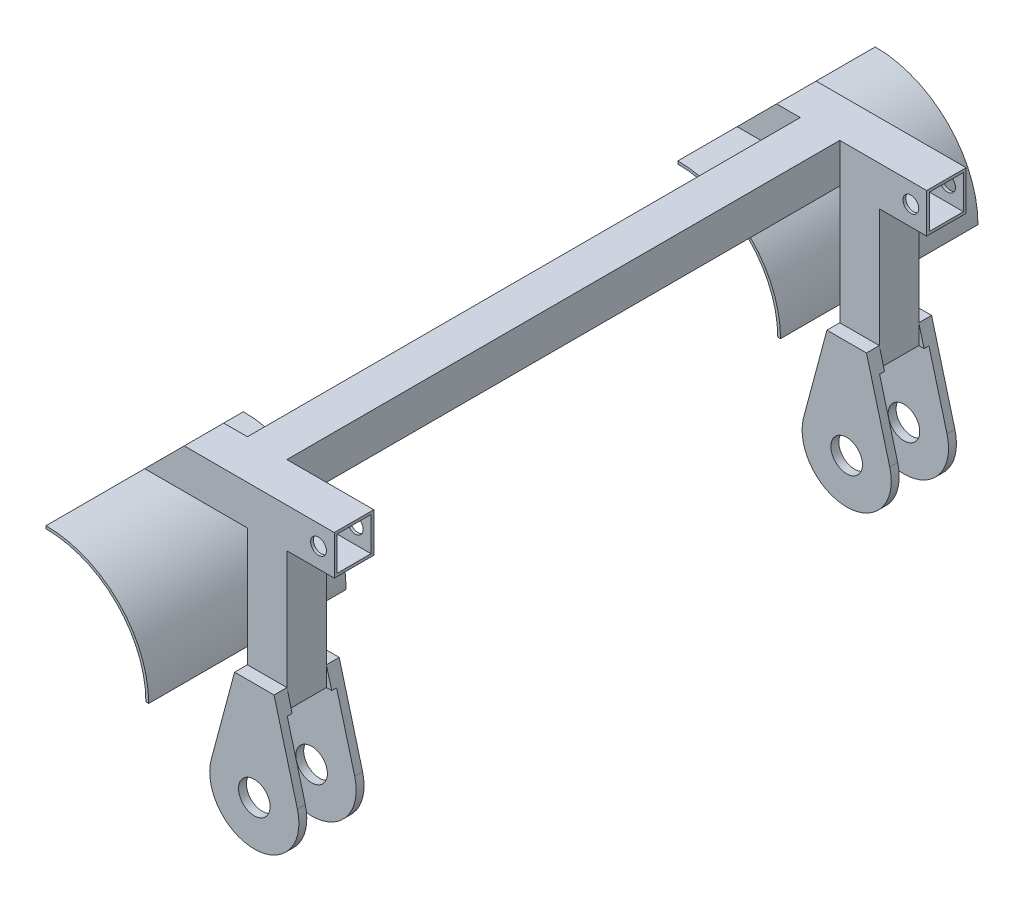
SolidWorks part; units mm, degrees
ref_plane "Front Plane" through (0, 0, 0) normal (0, 0, 1) x (1, 0, 0)
ref_plane "Top Plane" through (0, 0, 0) normal (0, 1, 0) x (1, 0, 0)
ref_plane "Right Plane" through (0, 0, 0) normal (1, 0, 0) x (0, 0, -1)
sketch "Sketch1" plane through (0, 0, 0) normal (0, 0, 1) x (1, 0, 0)
  line L0 (0, -11.2927) -> (0, 37.1736) construction
  line L1 (-5, 25) -> (5, 25)
  line L2 (-5, 25) -> (-10.9089, 2.9192)
  line L3 (5, 25) -> (10.9089, 2.9192)
  circle A0 centre (0, 0) radius 4
  arc A1 (-10.9089, 2.9192) -> (10.9089, 2.9192) centre (0, 0) ccw
  point P9 (0, 25)
  dimension "D1" = 8
  dimension "D2" = 5
  dimension "D3" = 25
extrude "Boss-Extrude1" add sketch "Sketch1" along normal blind 2 and the other way blind 1.25
sketch "Sketch2" plane through (0, 0, 2) normal (0, 0, 1) x (1, 0, 0)
  line L0 (-5, 55) -> (-5, 20)
  line L1 (-5, 20) -> (5, 20)
  line L2 (5, 20) -> (5, 55)
  line L3 (5, 55) -> (-5, 55)
  line L4 (5, 25) -> (-5, 25) construction
  dimension "D1" = 55
  dimension "D2" = 5
extrude "Boss-Extrude2" add sketch "Sketch2" along normal blind 10
ref_plane "Plane1" through (0, 0, 7) normal (0, 0, 1) x (1, 0, 0)
mirror "Mirror1" about plane through (0, 0, 7) normal (0, 0, 1) of bodies 102
ref_plane "Plane2" through (17, 0, 0) normal (1, 0, 0) x (0, 0, -1)
sketch "Sketch4" plane through (17, 0, 0) normal (1, 0, 0) x (0, 0, -1)
  line L0 (-11.3, 64.3) -> (-2.7, 64.3)
  line L1 (-12, 55) -> (-2, 55)
  line L2 (-12, 55) -> (-12, 65)
  line L3 (-12, 65) -> (-2, 65)
  line L4 (-2, 55) -> (-2, 65)
  line L5 (-2.7, 55.7) -> (-2.7, 64.3)
  line L6 (-11.3, 55.7) -> (-2.7, 55.7)
  line L7 (-11.3, 55.7) -> (-11.3, 64.3)
  dimension "D1" = 10
  dimension "D2" = 10
  dimension "D3" = 0.7
extrude "Boss-Extrude3" add sketch "Sketch4" against normal blind 48
sketch "Sketch5" plane through (0, 0, 12) normal (0, 0, 1) x (1, 0, 0)
  line L0 (17, -5.5) -> (17, 5.5) construction
  line L1 (5, 55) -> (17, 55) construction
  circle A0 centre (13, 60) radius 2
  dimension "D1" = 4
  dimension "D2" = 5
extrude "Cut-Extrude1" cut sketch "Sketch5" against normal blind 50
sketch "Sketch9" plane through (0, 0, 12) normal (0, 0, 1) x (1, 0, 0)
  line L0 (-5, 55) -> (-5, 25) construction
  line L1 (-31, 55) -> (-5, 55)
  line L2 (-31, 55) -> (-31, 54.3)
  line L3 (-5.7, 29) -> (-5, 29)
  line L4 (-5, 55) -> (-5, 29)
  arc A0 (-5, 29) -> (-31, 55) centre (-31, 29) ccw
  arc A1 (-5.7, 29) -> (-31, 54.3) centre (-31, 29) ccw
  circle A2 centre (-31, 29) radius 26 construction
  circle A3 centre (-31, 29) radius 25.3 construction
  dimension "D1" = 26
  dimension "D2" = 0.7
extrude "Boss-Extrude4" add sketch "Sketch9" along normal mid plane 50 separate body contours A1 L3 A0 L2
sketch "Sketch10" plane through (0, 0, 12) normal (0, 0, 1) x (1, 0, 0)
  line L0 (-31, 65) -> (-31, 55)
  line L1 (-31, 55) -> (-21, 65)
  line L2 (-31, 65) -> (17, 65) construction
  line L3 (-21, 65) -> (-31, 65)
extrude "Cut-Extrude2" cut sketch "Sketch10" against normal blind 50
ref_plane "Plane3" through (0, 0, -68) normal (0, 0, -1) x (-1, 0, 0)
sketch "Sketch14" plane through (5, 0, 0) normal (1, 0, 0) x (0, 0, -1)
  line L1 (-2, 20) -> (-0.75, 20)
  line L2 (-2, 20) -> (-2, -14.9033)
  line L3 (-2, -14.9033) -> (-0.75, -14.9033)
  line L4 (-0.75, 20) -> (-0.75, -14.9033)
  line L5 (-12, 20) -> (-13.25, 20)
  line L6 (-12, 20) -> (-12, -16.0888)
  line L7 (-12, -16.0888) -> (-13.25, -16.0888)
  line L8 (-13.25, 20) -> (-13.25, -16.0888)
  dimension "D1" = 1.25
  dimension "D2" = 1.25
extrude "Cut-Extrude3" cut sketch "Sketch14" against normal blind 26 and the other way blind 31
mirror "Mirror2" about plane through (0, 0, -68) normal (0, 0, -1) of bodies 112 106
sketch "Sketch15" plane through (0, 0, 2) normal (0, 0, -1) x (-1, 0, 0)
  line L0 (21, 65) -> (-17, 65) construction
  line L1 (5, 55) -> (15, 55)
  line L2 (5, 55) -> (5, 65)
  line L3 (5, 65) -> (15, 65)
  line L4 (15, 55) -> (15, 65)
  dimension "D1" = 10
extrude "Boss-Extrude7" add sketch "Sketch15" along normal up to vertex
